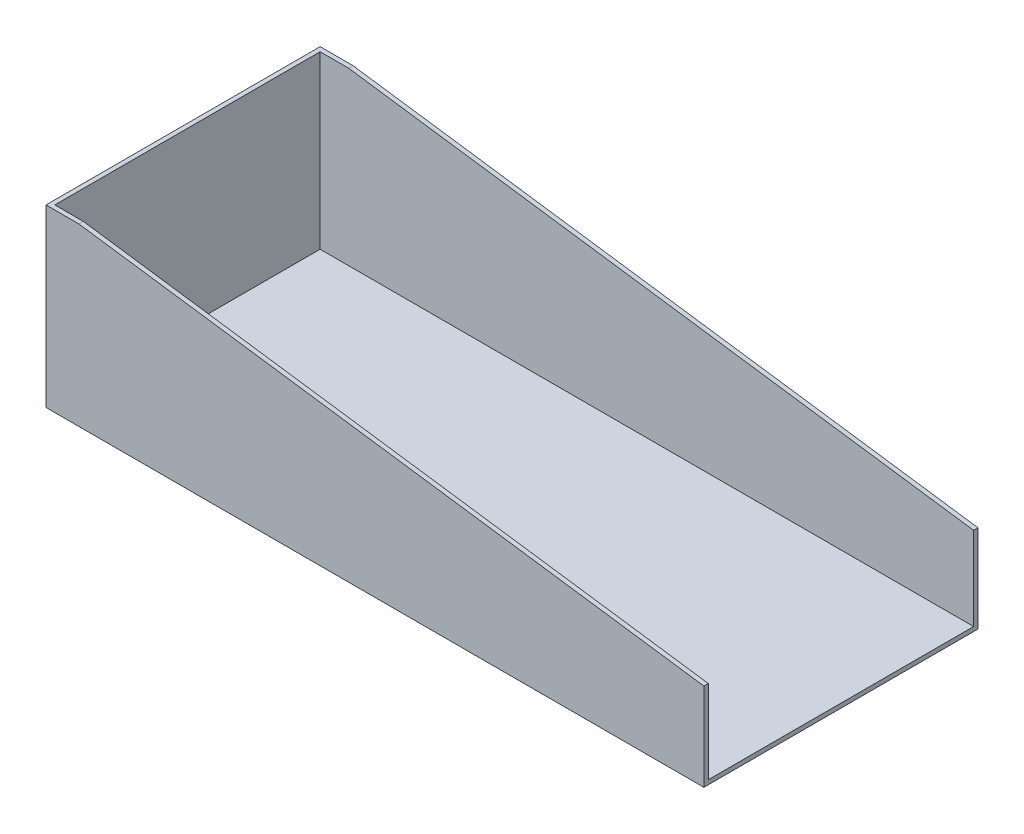
SolidWorks part; units mm, degrees
ref_plane "Front Plane" through (0, 0, 0) normal (0, 0, 1) x (1, 0, 0)
ref_plane "Top Plane" through (0, 0, 0) normal (0, 1, 0) x (1, 0, 0)
ref_plane "Right Plane" through (0, 0, 0) normal (1, 0, 0) x (0, 0, -1)
sketch "Sketch1" plane through (0, 0, 0) normal (0, 1, 0) x (1, 0, 0)
  line L1 (0, 0) -> (-300, 0)
  line L2 (0, 0) -> (0, 125)
  line L3 (0, 125) -> (-300, 125)
  line L4 (-300, 0) -> (-300, 125)
  dimension "D1" = 125
  dimension "D2" = 300
extrude "Boss-Extrude2" add sketch "Sketch1" along normal blind 80
sketch "Sketch3" plane through (0, 0, 0) normal (0, 0, 1) x (1, 0, 0)
  line L0 (-285, 80) -> (0, 40)
  line L1 (-300, 80) -> (0, 80) construction
  line L2 (0, 80) -> (0, 0) construction
  line L4 (-300, 80) -> (0, 80)
  line L5 (-300, 80) -> (-300, 0)
  line L6 (-300, 0) -> (0, 0)
  line L7 (0, 80) -> (0, 0)
  dimension "D1" = 15
extrude "Cut-Extrude2" cut sketch "Sketch3" against normal blind 135 contours L2 L0 L1
shell "Shell2" thickness 2
